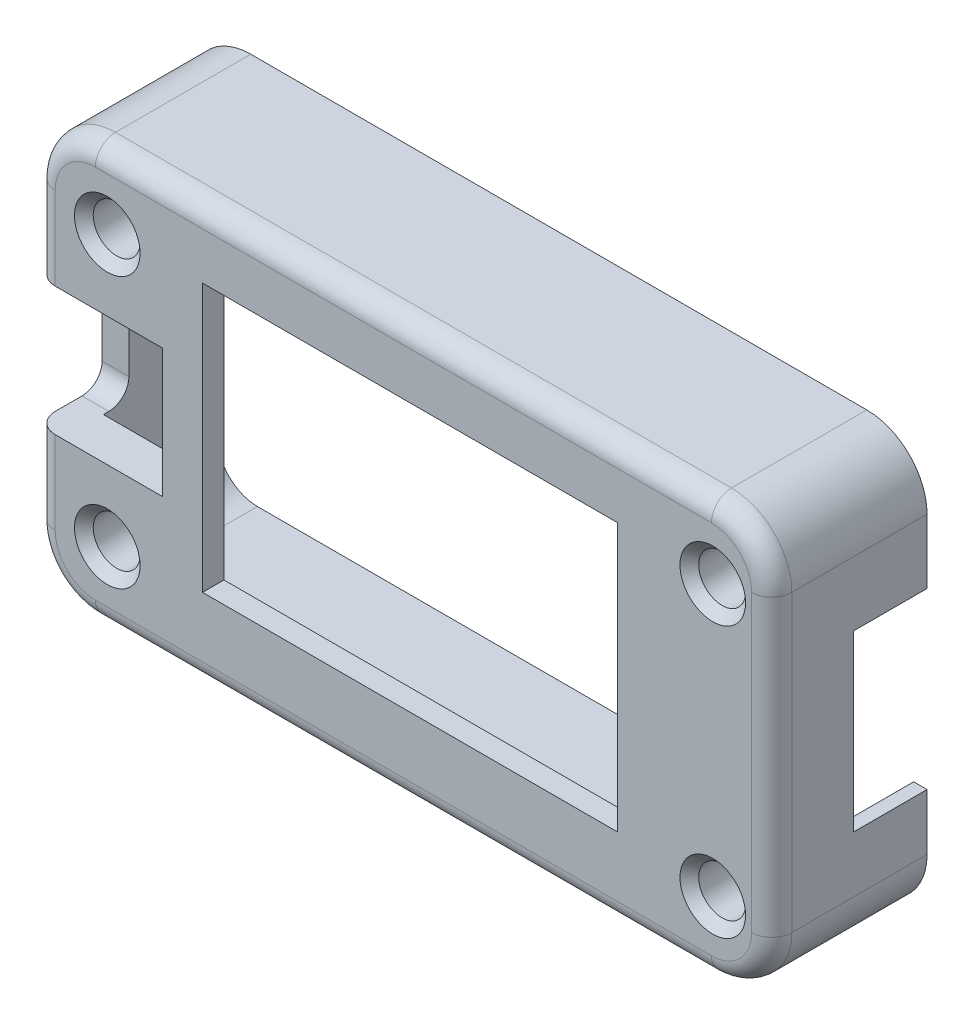
SolidWorks part; units mm, degrees
ref_plane "前视基准面" through (0, 0, 0) normal (0, 0, 1) x (1, 0, 0)
ref_plane "上视基准面" through (0, 0, 0) normal (0, 1, 0) x (1, 0, 0)
ref_plane "右视基准面" through (0, 0, 0) normal (1, 0, 0) x (0, 0, -1)
sketch "草图1" plane through (0, 0, 0) normal (0, 0, 1) x (1, 0, 0)
  line L0 (0, 0) -> (55, 0)
  line L1 (55, 0) -> (55, -31)
  line L2 (55, -31) -> (0, -31)
  line L3 (0, -31) -> (0, 0)
  line L4 (2, -2) -> (54, -2)
  line L5 (54, -2) -> (54, -29)
  line L6 (54, -29) -> (2, -29)
  line L7 (2, -29) -> (2, -2)
  dimension "D1" = 52
  dimension "D2" = 27
  dimension "D3" = 1
  dimension "D4" = 2
  dimension "D5" = 2
  dimension "D6" = 2
extrude "凸台-拉伸1" add sketch "草图1" along normal blind 10
sketch "草图2" plane through (0, 0, 10) normal (0, 0, 1) x (1, 0, 0)
  line L0 (55, -31) -> (55, 0) construction
  line L1 (0, -31) -> (55, -31) construction
  line L2 (0, 0) -> (0, -31) construction
  line L3 (55, 0) -> (0, 0) construction
  line L4 (55, -31) -> (55, 0)
  line L5 (0, -31) -> (55, -31)
  line L6 (0, 0) -> (0, -31)
  line L7 (55, 0) -> (0, 0)
extrude "凸台-拉伸2" add sketch "草图2" along normal blind 1.6
sketch "草图3" plane through (0, 0, 11.6) normal (0, 0, 1) x (1, 0, 0)
  line L0 (12.5, -5) -> (43.5, -5)
  line L1 (43.5, -5) -> (43.5, -25)
  line L2 (43.5, -25) -> (12.5, -25)
  line L3 (12.5, -25) -> (12.5, -5)
  line L4 (0, 0) -> (0, -31) construction
  line L8 (0, -31) -> (55, -31) construction
  dimension "D1" = 31
  dimension "D2" = 20
  dimension "D3" = 12.5
  dimension "D4" = 6
extrude "切除-拉伸1" cut sketch "草图3" against normal up to next
sketch "草图4" plane through (0, 0, 10) normal (0, 0, -1) x (-1, 0, 0)
  line L0 (-45.5, -3) -> (-10.5, -3)
  line L1 (-10.5, -3) -> (-10.5, -27)
  line L2 (-10.5, -27) -> (-45.5, -27)
  line L3 (-45.5, -27) -> (-45.5, -3)
  line L4 (-2, -29) -> (-54, -29) construction
  line L5 (-54, -29) -> (-54, -2) construction
  line L6 (-54, -2) -> (-2, -2) construction
  line L7 (-2, -2) -> (-2, -29) construction
  line L8 (-2, -29) -> (-54, -29)
  line L9 (-54, -29) -> (-54, -2)
  line L10 (-54, -2) -> (-2, -2)
  line L11 (-2, -2) -> (-2, -29)
  line L13 (-12.5, -25) -> (-12.5, -5) construction
  line L14 (-43.5, -5) -> (-43.5, -25) construction
  dimension "D1" = 1
  dimension "D2" = 2
  dimension "D3" = 2
  dimension "D4" = 2
extrude "凸台-拉伸3" add sketch "草图4" along normal blind 1.5
sketch "草图5" plane through (0, 0, 8.5) normal (0, 0, -1) x (-1, 0, 0)
  line L0 (-35.5, -27) -> (-20.5, -27)
  line L1 (-45.5, -27) -> (-10.5, -27) construction
  line L2 (-20.5, -27) -> (-20.5, -29)
  line L3 (-2, -29) -> (-54, -29) construction
  line L4 (-20.5, -29) -> (-35.5, -29)
  line L5 (-35.5, -29) -> (-35.5, -27)
  line L6 (-45.5, -3) -> (-45.5, -27) construction
  line L7 (-10.5, -27) -> (-10.5, -3) construction
  dimension "D1" = 10
  dimension "D2" = 10
extrude "切除-拉伸2" cut sketch "草图5" against normal blind 1.5
sketch "草图7" plane through (0, 0, 11.6) normal (0, 0, 1) x (1, 0, 0)
  line L0 (0, -10.7) -> (9.5, -10.7)
  line L1 (0, 0) -> (0, -31) construction
  line L2 (9.5, -10.7) -> (9.5, -20.3)
  line L3 (9.5, -20.3) -> (0, -20.3)
  line L4 (0, -20.3) -> (0, -10.7)
  line L5 (55, 0) -> (0, 0) construction
  dimension "D1" = 9.6
  dimension "D2" = 10.7
  dimension "D3" = 9.5
extrude "切除-拉伸4" cut sketch "草图7" against normal blind 5
sketch "草图8" plane through (0, 0, 8.5) normal (0, 0, -1) x (-1, 0, 0)
  line L0 (-9.5, -10.7) -> (-10.5, -10.7)
  line L1 (-10.5, -27) -> (-10.5, -3) construction
  line L2 (-10.5, -10.7) -> (-10.5, -20.3)
  line L3 (-10.5, -27) -> (-10.5, -3) construction
  line L4 (-10.5, -20.3) -> (-9.5, -20.3)
  line L5 (-9.5, -20.3) -> (-9.5, -10.7)
extrude "切除-拉伸5" cut sketch "草图8" against normal blind 1.5
sketch "草图9" plane through (0, 0, 0) normal (0, 0, -1) x (-1, 0, 0)
  line L0 (-55, -9.3) -> (-54, -9.3)
  line L1 (-55, -31) -> (-55, 0) construction
  line L2 (-54, -29) -> (-54, -2) construction
  line L3 (-54, -9.3) -> (-54, -22.3)
  line L4 (-54, -22.3) -> (-55, -22.3)
  line L5 (-55, -22.3) -> (-55, -9.3)
  line L6 (-54, -2) -> (-2, -2) construction
  dimension "D1" = 13
  dimension "D2" = 7.3
extrude "切除-拉伸6" cut sketch "草图9" against normal blind 5.5
sketch "草图10" plane through (0, 0, 8.5) normal (0, 0, -1) x (-1, 0, 0)
  line L0 (-54, -2) -> (-54, -29) construction
  line L2 (-54, -2) -> (-2, -2) construction
  circle A0 centre (-50.6, -5.4) radius 1.75
  circle A1 centre (-5.388, -5.4) radius 1.75
  circle A2 centre (-5.388, -25.6) radius 1.75
  circle A3 centre (-50.6, -25.6) radius 1.75
  dimension "D1" = 45.212
  dimension "D3" = 3.5
  dimension "D2" = 20.2
  dimension "D4" = 3.4
  dimension "D5" = 3.4
extrude "切除-拉伸7" cut sketch "草图10" against normal through all
fillet "圆角1" radius 3 4 edges at (2, -29, 4.25) (54, -29, 4.25) (54, -2, 4.25) (2, -2, 4.25)
fillet "圆角2" radius 4.5 4 edges at (0, 0, 5.8) (0, -31, 5.8) (55, -31, 5.8) (55, 0, 5.8)
fillet "圆角3" radius 1.5 2 edges at (1, -20.3, 6.6) (1, -10.7, 6.6)
fillet "圆角4" radius 1.5 9 edges at (0, -23.4, 11.6) (1.318, -29.682, 11.6) (0, -7.6, 11.6) (1.318, -1.318, 11.6) (27.5, 0, 11.6) (53.682, -1.318, 11.6) (55, -15.5, 11.6) (53.682, -29.682, 11.6) (27.5, -31, 11.6)
chamfer "倒角1" distance 0.7 angle 45 4 edges at (3.638, -5.4, 11.6) (3.638, -25.6, 11.6) (48.85, -5.4, 11.6) (48.85, -25.6, 11.6)
